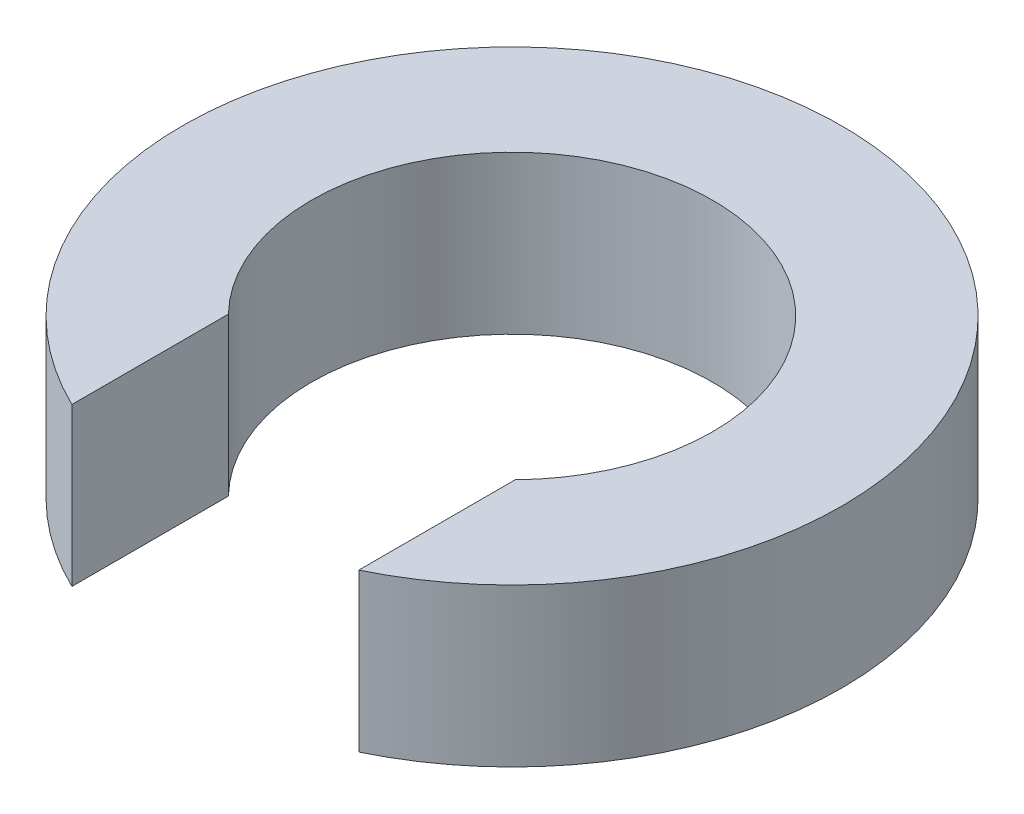
SolidWorks part; units mm, degrees
ref_plane "Alzado" through (0, 0, 0) normal (0, 0, 1) x (1, 0, 0)
ref_plane "Planta" through (0, 0, 0) normal (0, 1, 0) x (1, 0, 0)
ref_plane "Vista lateral" through (0, 0, 0) normal (1, 0, 0) x (0, 0, -1)
sketch "Croquis1" plane through (0, 0, 0) normal (0, 1, 0) x (1, 0, 0)
  circle A2 centre (0, 0) radius 11.5
  circle A3 centre (0, 0) radius 7
  dimension "D1" = 23
  dimension "D2" = 14
extrude "Saliente-Extruir1" add sketch "Croquis1" along normal blind 5.5
sketch "Croquis2" plane through (0, 5.5, 0) normal (0, 1, 0) x (1, 0, 0)
  line L0 (-5.0052, -4.8936) -> (-5.0052, -10.3536) construction
  line L1 (0, 11.5) -> (0, 0) construction
  line L2 (5.0052, -4.8936) -> (5.0052, -10.3536) construction
  line L4 (-5.0052, -4.8936) -> (5.0052, -4.8936)
  line L5 (-5.0052, -4.8936) -> (-5.0052, -11.5)
  line L6 (-5.0052, -11.5) -> (5.0052, -11.5)
  line L7 (5.0052, -4.8936) -> (5.0052, -11.5)
  circle A0 centre (0, 0) radius 7 construction
  circle A1 centre (0, 0) radius 11.5 construction
  dimension "D1" = 5.46
extrude "Cortar-Extruir1" cut sketch "Croquis2" against normal through all
